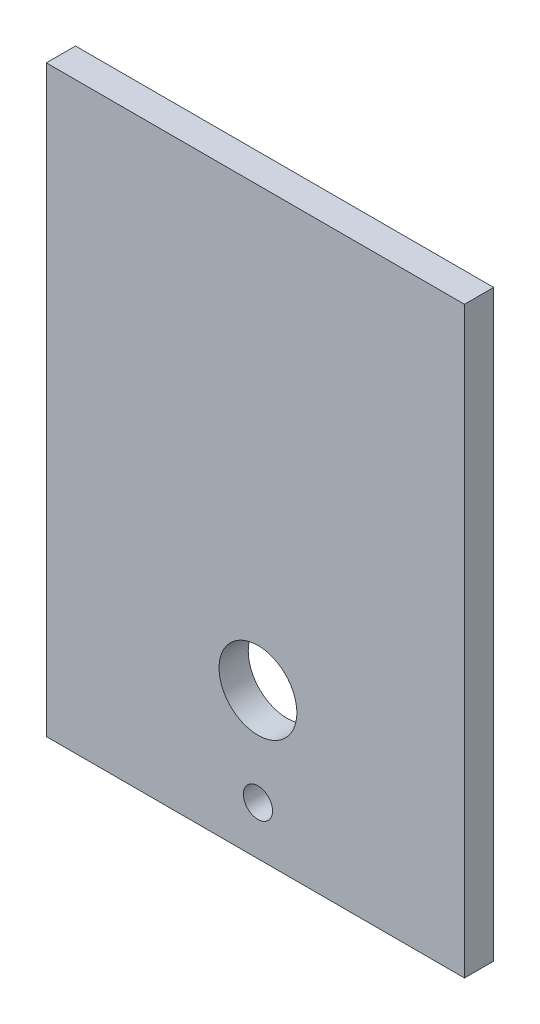
SolidWorks part; units mm, degrees
ref_plane "Front Plane" through (0, 0, 0) normal (0, 0, 1) x (1, 0, 0)
ref_plane "Top Plane" through (0, 0, 0) normal (0, 1, 0) x (1, 0, 0)
ref_plane "Right Plane" through (0, 0, 0) normal (1, 0, 0) x (0, 0, -1)
sketch "Sketch1" plane through (0, 0, 0) normal (0, 0, 1) x (1, 0, 0)
  line L1 (0, 0) -> (1092.2, 0)
  line L2 (0, 0) -> (0, 1524)
  line L3 (0, 1524) -> (1092.2, 1524)
  line L4 (1092.2, 0) -> (1092.2, 1524)
  circle A0 centre (552.718, 381) radius 101.6
  circle A1 centre (552.718, 127) radius 38.1
  dimension "D3" = 203.2
  dimension "D6" = 76.2
  dimension "D1" = 1092.2
  dimension "D2" = 1524
  dimension "D4" = 539.482
  dimension "D5" = 381
  dimension "D7" = 127
extrude "Boss-Extrude1" add sketch "Sketch1" along normal blind 76.2
